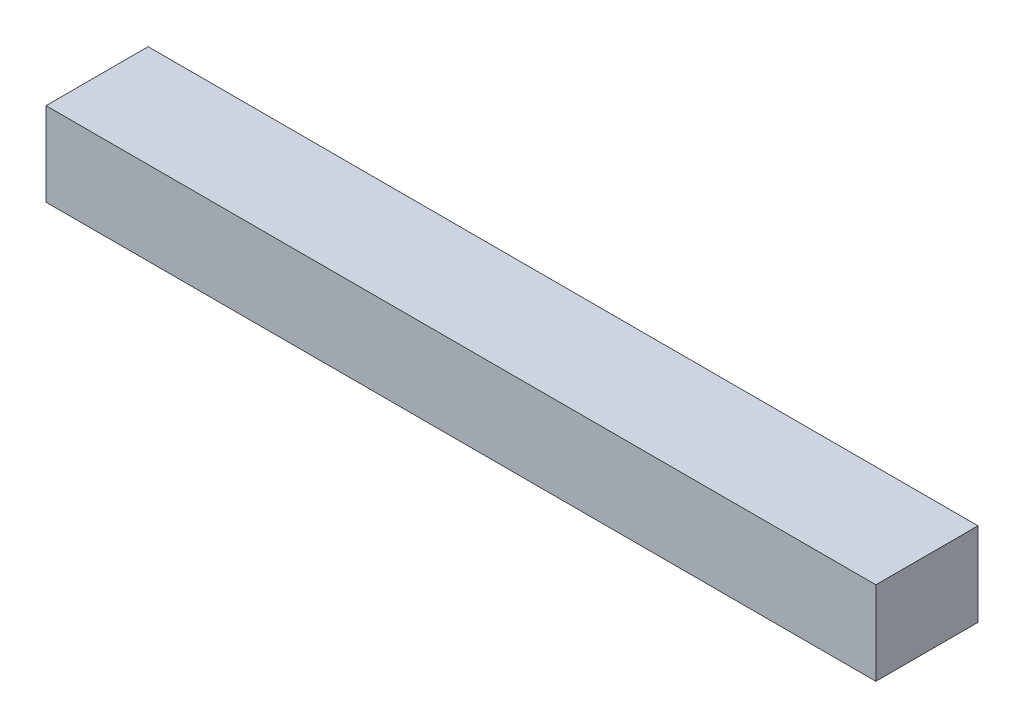
SolidWorks part; units mm, degrees
ref_plane "前视基准面" through (0, 0, 0) normal (0, 0, 1) x (1, 0, 0)
ref_plane "上视基准面" through (0, 0, 0) normal (0, 1, 0) x (1, 0, 0)
ref_plane "右视基准面" through (0, 0, 0) normal (1, 0, 0) x (0, 0, -1)
sketch "草图1" plane through (0, 0, 0) normal (1, 0, 0) x (0, 0, -1)
  line L1 (0, 0) -> (320, 0)
  line L2 (0, 0) -> (0, 262)
  line L3 (0, 262) -> (320, 262)
  line L4 (320, 0) -> (320, 262)
  dimension "D1" = 262
  dimension "D2" = 320
extrude "凸台-拉伸1" add sketch "草图1" along normal blind 2600
